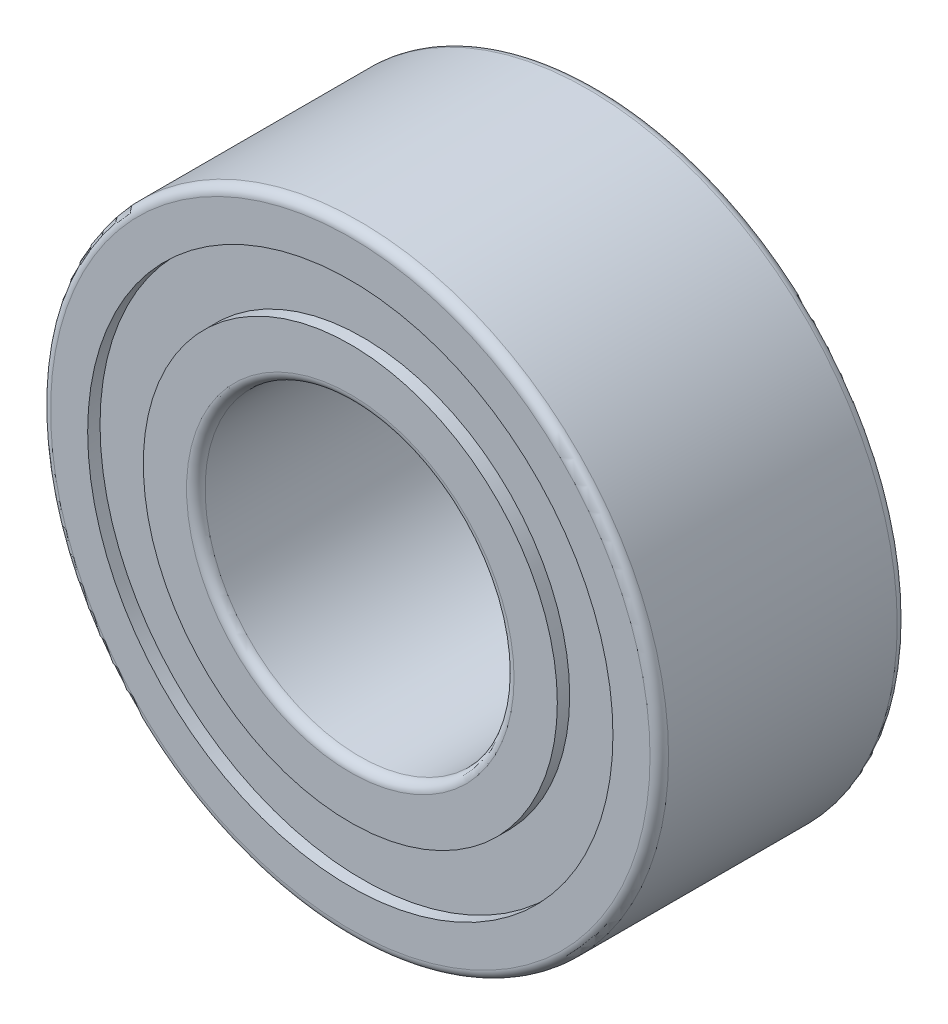
SolidWorks part; units mm, degrees
material "普通碳钢"
ref_plane "前视基准面" through (0, 0, 0) normal (0, 0, 1) x (1, 0, 0)
ref_plane "上视基准面" through (0, 0, 0) normal (0, 1, 0) x (1, 0, 0)
ref_plane "右视基准面" through (0, 0, 0) normal (1, 0, 0) x (0, 0, -1)
sketch "草图1" plane through (0, 0, 0) normal (0, 0, 1) x (1, 0, 0)
  circle A0 centre (0, 0) radius 2.5
  circle A1 centre (0, 0) radius 5
  dimension "D1" = 5
  dimension "D2" = 10
extrude "拉伸1" add sketch "草图1" along normal mid plane 4
sketch "草图2" plane through (0, 0, 2) normal (0, 0, 1) x (1, 0, 0)
  circle A0 centre (0, 0) radius 3.35
  circle A1 centre (0, 0) radius 4.25
  dimension "D1" = 6.7
  dimension "D2" = 8.5
extrude "拉伸2" cut sketch "草图2" against normal blind 0.2
mirror "镜向1" about plane through (0, 0, 0) normal (0, 0, 1) of "拉伸2"
fillet "圆角1" radius 0.15 4 edges at (2.5, 0, -2) (5, 0, -2) (2.5, 0, 2) (5, 0, 2)
